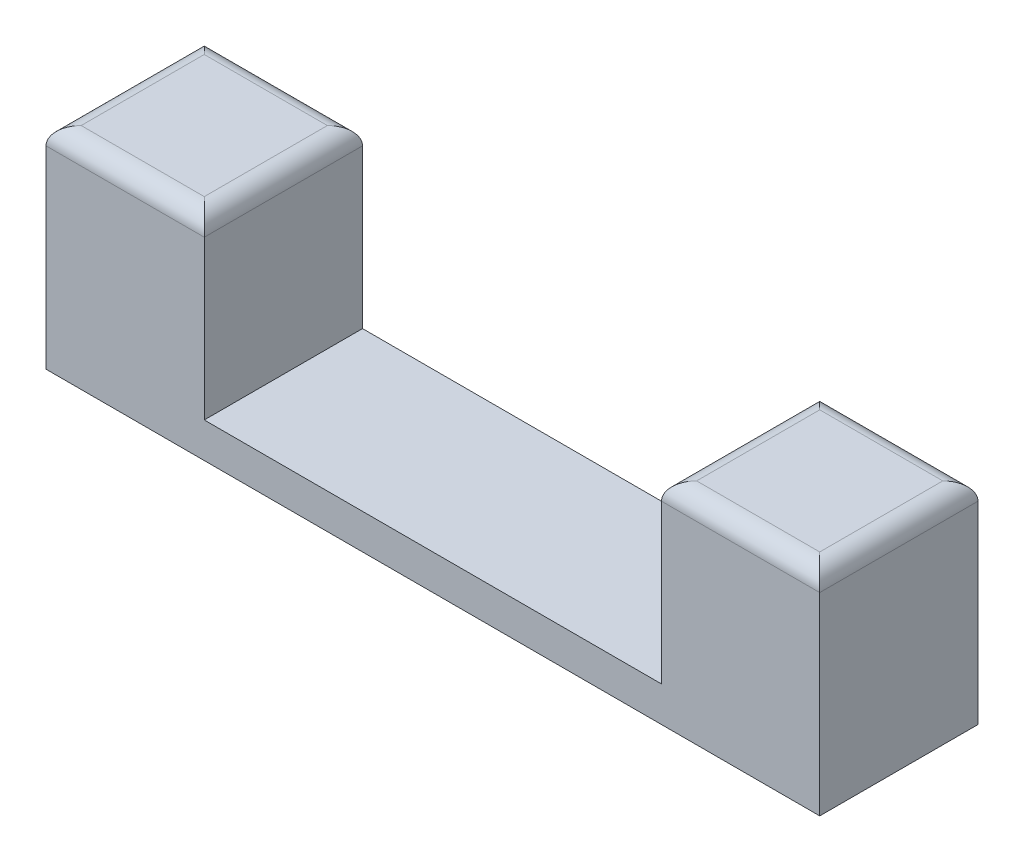
SolidWorks part; units mm, degrees
ref_plane "Front Plane" through (0, 0, 0) normal (0, 0, 1) x (1, 0, 0)
ref_plane "Top Plane" through (0, 0, 0) normal (0, 1, 0) x (1, 0, 0)
ref_plane "Right Plane" through (0, 0, 0) normal (1, 0, 0) x (0, 0, -1)
sketch "Sketch1" plane through (0, 0, 0) normal (0, 1, 0) x (1, 0, 0)
  line L1 (-11, 2.25) -> (11, 2.25)
  line L2 (-11, 2.25) -> (-11, -2.25)
  line L3 (-11, -2.25) -> (11, -2.25)
  line L4 (11, 2.25) -> (11, -2.25)
  line L5 (-11, 2.25) -> (11, -2.25) construction
  line L6 (-11, -2.25) -> (11, 2.25) construction
  point P0 (0, 0)
  dimension "D1" = 4.5
  dimension "D2" = 22
extrude "Boss-Extrude1" add sketch "Sketch1" along normal blind 1
sketch "Sketch2" plane through (0, 1, 0) normal (0, 1, 0) x (1, 0, 0)
  line L0 (-11, -2.25) -> (11, -2.25) construction
  line L1 (-11, 2.25) -> (-6.5, 2.25)
  line L2 (-11, 2.25) -> (-11, -2.25)
  line L3 (-11, -2.25) -> (-6.5, -2.25)
  line L4 (-6.5, 2.25) -> (-6.5, -2.25)
  line L6 (11, 2.25) -> (6.5, 2.25)
  line L7 (11, 2.25) -> (11, -2.25)
  line L8 (11, -2.25) -> (6.5, -2.25)
  line L9 (6.5, 2.25) -> (6.5, -2.25)
  dimension "D1" = 4.5
  dimension "D2" = 4.5
extrude "Boss-Extrude2" add sketch "Sketch2" along normal blind 5
fillet "Fillet1" radius 0.5 8 edges at (8.75, 6, -2.25) (11, 6, 0) (8.75, 6, 2.25) (6.5, 6, 0) (-6.5, 6, 0) (-8.75, 6, 2.25) (-11, 6, 0) (-8.75, 6, -2.25)
